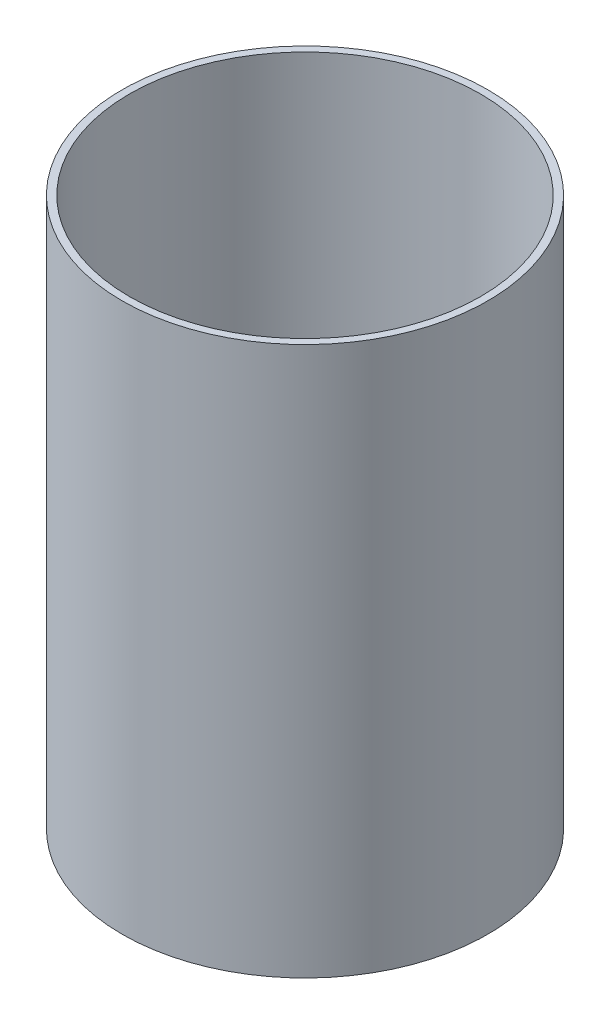
SolidWorks part; units mm, degrees
ref_plane "Front Plane" through (0, 0, 0) normal (0, 0, 1) x (1, 0, 0)
ref_plane "Top Plane" through (0, 0, 0) normal (0, 1, 0) x (1, 0, 0)
ref_plane "Right Plane" through (0, 0, 0) normal (1, 0, 0) x (0, 0, -1)
sketch "Sketch1" plane through (0, 0, 0) normal (0, 1, 0) x (1, 0, 0)
  circle A0 centre (0, 0) radius 50
  circle A1 centre (0, 0) radius 48
extrude "Boss-Extrude2" add sketch "Sketch1" along normal blind 150
